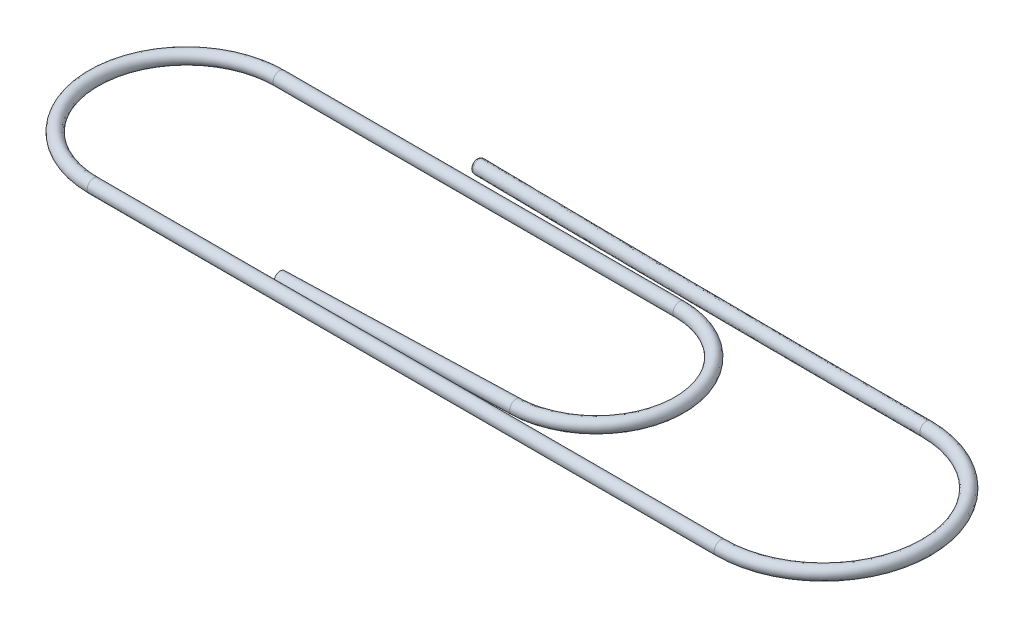
SolidWorks part; units mm, degrees
material "Chrome Stainless Steel"
ref_plane "Front Plane" through (0, 0, 0) normal (0, 0, 1) x (1, 0, 0)
ref_plane "Top Plane" through (0, 0, 0) normal (0, 1, 0) x (1, 0, 0)
ref_plane "Right Plane" through (0, 0, 0) normal (1, 0, 0) x (0, 0, -1)
sketch "Sketch1" plane through (0, 0, 0) normal (0, 1, 0) x (1, 0, 0)
  line L2 (19.1189, -7.1739) -> (10.2927, -7.451)
  line L5 (27.7812, -7.9375) -> (3.5877, -7.9375)
  line L12 (3.5877, -0.762) -> (19.0183, -0.762)
  arc A0 (27.7812, -7.9375) -> (27.7812, 0) centre (27.7812, -3.9688) ccw
  arc A1 (3.5877, -0.762) -> (3.5877, -7.9375) centre (3.5877, -4.3497) ccw
  arc A2 (19.1189, -7.1739) -> (19.0183, -0.762) centre (19.0183, -3.9687) ccw
  spline S0 degree 2 poles (27.7812, 0) (19.0367, 0) (10.2927, 0.141) knots 0 0 0 1 1 1
ref_plane "Plane2" through (10.2927, 0, 0) normal (1, 0, 0) x (0, 0, -1)
sketch "Sketch3" plane through (10.2927, 0, 0) normal (1, 0, 0) x (0, 0, -1)
  circle A0 centre (0.141, 0) radius 0.25
sweep "Sweep2" add profiles "Sketch3" path "Sketch1"
fillet "Fillet1" radius 0.1026 1 edges at (10.2927, 0, -0.391)
